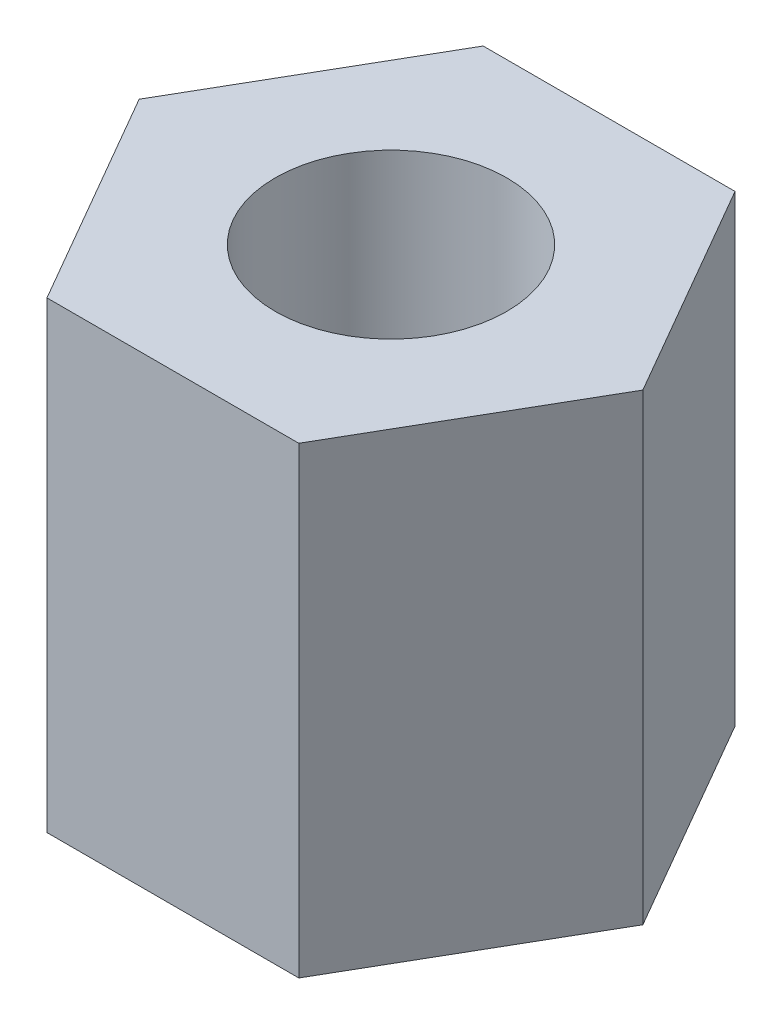
SolidWorks part; units mm, degrees
material "黄铜"
ref_plane "前视基准面" through (0, 0, 0) normal (0, 0, 1) x (1, 0, 0)
ref_plane "上视基准面" through (0, 0, 0) normal (0, 1, 0) x (1, 0, 0)
ref_plane "右视基准面" through (0, 0, 0) normal (1, 0, 0) x (0, 0, -1)
sketch "草图1" plane through (0, 0, 0) normal (0, 1, 0) x (1, 0, 0)
  line L0 (0, 3.661) -> (0, -3.0076) construction
  line L1 (-5.2561, 0) -> (6.6398, 0) construction
  line L3 (2.7193, 0) -> (1.3597, 2.355)
  line L4 (1.3597, 2.355) -> (-1.3597, 2.355)
  line L5 (-1.3597, 2.355) -> (-2.7193, 0)
  line L6 (-2.7193, 0) -> (-1.3597, -2.355)
  line L7 (-1.3597, -2.355) -> (1.3597, -2.355)
  line L8 (1.3597, -2.355) -> (2.7193, 0)
  circle A0 centre (0, 0) radius 2.355 construction
  dimension "D1" = 4.71
extrude "凸台-拉伸1" add sketch "草图1" along normal blind 5
sketch "草图2" plane through (0, 5, 0) normal (0, 1, 0) x (1, 0, 0)
  point P0 (0, 0)
hole_wizard "M3 螺纹孔1" positions "草图3" profile "草图4" tap size "M3" standard "GB" end condition through all
sketch "草图3" plane through (0, 5, 0) normal (0, 1, 0) x (1, 0, 0)
  point P0 (0, 0)
  point P3 (0, 0)
sketch "草图4" plane through (0, 5, 0) normal (1, 0, 0) x (0, 0, 1)
  line L0 (0, 0) -> (0, 5)
  line L1 (0, 5) -> (1.25, 5)
  line L2 (1.25, 5) -> (1.25, 0)
  line L5 (1.25, 0) -> (0, 0)
  line L11 (0, -6.35) -> (0, 107.95) construction
  dimension "通孔螺纹孔钻头直径" = 2.5
  dimension "通孔螺纹孔钻头深度" = 5
cosmetic thread "孔螺蚊线1"
